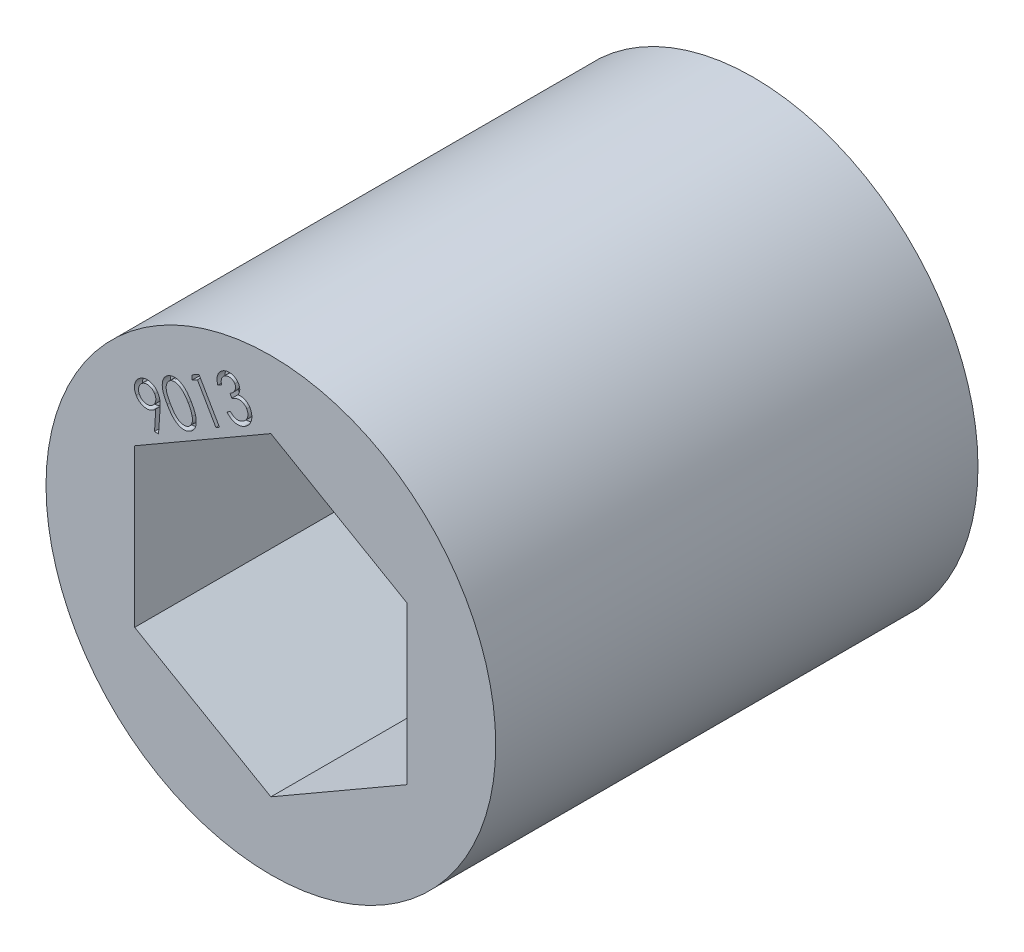
SolidWorks part; units mm, degrees
material "ABS"
ref_plane "Front Plane" through (0, 0, 0) normal (0, 0, 1) x (1, 0, 0)
ref_plane "Top Plane" through (0, 0, 0) normal (0, 1, 0) x (1, 0, 0)
ref_plane "Right Plane" through (0, 0, 0) normal (1, 0, 0) x (0, 0, -1)
sketch "Sketch1" plane through (0, 0, 0) normal (0, 0, 1) x (1, 0, 0)
  line L1 (0, 7.7723) -> (-6.731, 3.8861)
  line L2 (-6.731, 3.8861) -> (-6.731, -3.8861)
  line L3 (-6.731, -3.8861) -> (0, -7.7723)
  line L4 (0, -7.7723) -> (6.731, -3.8861)
  line L5 (6.731, -3.8861) -> (6.731, 3.8861)
  line L6 (6.731, 3.8861) -> (0, 7.7723)
  circle A0 centre (0, 0) radius 6.731 construction
  circle A1 centre (0, 0) radius 11.1125
  dimension "D1" = 13.462
  dimension "D2" = 22.225
extrude "Boss-Extrude1" add sketch "Sketch1" along normal blind 23.8316 contours A1 L6 L5 L4 L3 L2 L1
sketch "Sketch2" plane through (0, 0, 23.8316) normal (0, 0, 1) x (1, 0, 0)
  line L0 (-6.0464, 4.7507) -> (0.6846, 8.6368) construction
  line L1 (0, 7.7723) -> (-6.731, 3.8861) construction
  text T0 "9013\r\n\r\n" font "Century Gothic" height 2.032
  dimension "D1" = 0.4064
extrude "Cut-Extrude1" cut sketch "Sketch2" against normal blind 0.4
